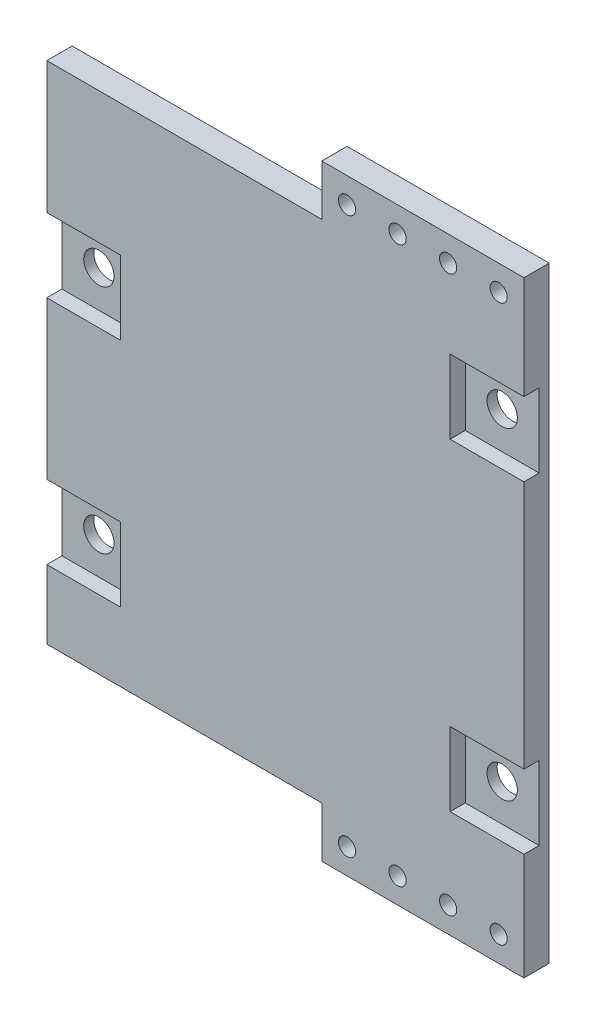
SolidWorks part; units mm, degrees
ref_plane "Front Plane" through (0, 0, 0) normal (0, 0, 1) x (1, 0, 0)
ref_plane "Top Plane" through (0, 0, 0) normal (0, 1, 0) x (1, 0, 0)
ref_plane "Right Plane" through (0, 0, 0) normal (1, 0, 0) x (0, 0, -1)
sketch "Sketch2" plane through (0, 0, 0) normal (0, 0, 1) x (1, 0, 0)
  line L0 (162.3349, 118.2403) -> (67.9349, 118.2403)
  line L1 (67.9349, 18.2403) -> (159.9349, 18.2403)
  line L2 (67.9349, 18.2403) -> (67.9349, 118.2403)
  line L3 (67.9349, 118.2403) -> (159.9349, 118.2403)
  line L4 (159.9349, 18.2403) -> (159.9349, 118.2403)
  line L5 (159.9349, 118.2403) -> (162.3349, 118.2403)
  line L6 (159.9349, 118.2403) -> (159.9349, 18.2403)
  line L7 (159.9349, 18.2403) -> (162.3349, 18.2403)
  line L8 (162.3349, 118.2403) -> (162.3349, 18.2403)
  line L9 (115.1349, 118.2403) -> (115.1349, 18.2403) construction
  line L10 (162.3349, 68.2403) -> (67.9349, 68.2403) construction
  circle A0 centre (75.2349, 84.9003) radius 3
  circle A1 centre (155.0349, 100.5603) radius 3
  circle A2 centre (155.0349, 36.7403) radius 3
  circle A3 centre (75.2349, 39.1803) radius 3
  dimension "D1" = 92
  dimension "D2" = 100
  dimension "D3" = 2.4
extrude "Boss-Extrude1" add sketch "Sketch2" along normal blind 2 contours L1 L4 L0 L2 A3 A2 A1 A0 | L8 L0 L4 L7
sketch "Sketch3" plane through (0, 0, 2) normal (0, 0, 1) x (1, 0, 0)
  line L0 (162.3349, 118.2403) -> (162.3349, 18.2403) construction
  line L1 (67.9349, 77.6003) -> (82.5349, 77.6003)
  line L2 (67.9349, 77.6003) -> (67.9349, 92.2003)
  line L3 (67.9349, 92.2003) -> (82.5349, 92.2003)
  line L4 (82.5349, 77.6003) -> (82.5349, 92.2003)
  line L5 (67.9349, 77.6003) -> (82.5349, 92.2003) construction
  line L6 (67.9349, 92.2003) -> (82.5349, 77.6003) construction
  line L7 (147.7349, 93.2603) -> (162.3349, 93.2603)
  line L8 (147.7349, 93.2603) -> (147.7349, 107.8603)
  line L9 (147.7349, 107.8603) -> (162.3349, 107.8603)
  line L10 (162.3349, 93.2603) -> (162.3349, 107.8603)
  line L11 (147.7349, 93.2603) -> (162.3349, 107.8603) construction
  line L12 (147.7349, 107.8603) -> (162.3349, 93.2603) construction
  line L14 (67.9349, 31.8803) -> (82.5349, 31.8803)
  line L15 (67.9349, 31.8803) -> (67.9349, 46.4803)
  line L16 (67.9349, 46.4803) -> (82.5349, 46.4803)
  line L17 (82.5349, 31.8803) -> (82.5349, 46.4803)
  line L18 (67.9349, 31.8803) -> (82.5349, 46.4803) construction
  line L19 (67.9349, 46.4803) -> (82.5349, 31.8803) construction
  line L20 (147.7349, 29.4403) -> (162.3349, 29.4403)
  line L21 (147.7349, 29.4403) -> (147.7349, 44.0403)
  line L22 (147.7349, 44.0403) -> (162.3349, 44.0403)
  line L23 (162.3349, 29.4403) -> (162.3349, 44.0403)
  line L24 (147.7349, 29.4403) -> (162.3349, 44.0403) construction
  line L25 (147.7349, 44.0403) -> (162.3349, 29.4403) construction
  line L26 (67.9349, 118.2403) -> (162.3349, 118.2403)
  line L27 (67.9349, 118.2403) -> (67.9349, 18.2403)
  line L28 (67.9349, 18.2403) -> (162.3349, 18.2403)
  line L29 (162.3349, 118.2403) -> (162.3349, 18.2403)
  point P0 (75.2349, 84.9003)
  point P5 (155.0349, 100.5603)
  point P14 (75.2349, 39.1803)
  point P19 (155.0349, 36.7403)
  line M9 (67.9349, 18.2403) -> (162.3349, 18.2403)
  line M10 (162.3349, 18.2403) -> (162.3349, 118.2403)
  line M11 (162.3349, 118.2403) -> (67.9349, 118.2403)
  line M12 (67.9349, 118.2403) -> (67.9349, 18.2403)
extrude "Boss-Extrude3" add sketch "Sketch3" along normal blind 3 contours L21 L22 L7 L8 L9 L3 L4 L1 L16 L17 L14 L20 M10 M11 M12 M9
sketch "Sketch5" plane through (0, 0, 0) normal (0, 0, -1) x (-1, 0, 0)
  line L0 (-67.9349, 18.2403) -> (-162.3349, 18.2403) construction
  point P0 (-124.6678, 4.7796)
  line B0 (-162.3349, 118.2403) -> (-122.3349, 118.2403)
  line B1 (-162.3349, 118.2403) -> (-162.3349, 128.2403)
  line B2 (-162.3349, 128.2403) -> (-122.3349, 128.2403)
  line B3 (-122.3349, 118.2403) -> (-122.3349, 128.2403)
  circle B4 centre (-157.3349, 123.2403) radius 1.7
  circle B5 centre (-147.3349, 123.2403) radius 1.7
  circle B6 centre (-137.3349, 123.2403) radius 1.7
  circle B7 centre (-127.3349, 123.2403) radius 1.7
  line B8 (-162.3349, 8.2403) -> (-122.3349, 8.2403)
  line B9 (-162.3349, 8.2403) -> (-162.3349, 18.2403)
  line B10 (-162.3349, 18.2403) -> (-122.3349, 18.2403)
  line B11 (-122.3349, 8.2403) -> (-122.3349, 18.2403)
  circle B12 centre (-157.3349, 13.2403) radius 1.7
  circle B13 centre (-147.3349, 13.2403) radius 1.7
  circle B14 centre (-137.3349, 13.2403) radius 1.7
  circle B15 centre (-127.3349, 13.2403) radius 1.7
sketch_block_instance "Block1-1"
sketch_block "Block1" parameters "D2"=3.4, "D1"=10, "D3"=5, "D4"=40
sketch_block_instance "Block1-2"
extrude "Boss-Extrude4" add sketch "Sketch5" against normal blind 5
